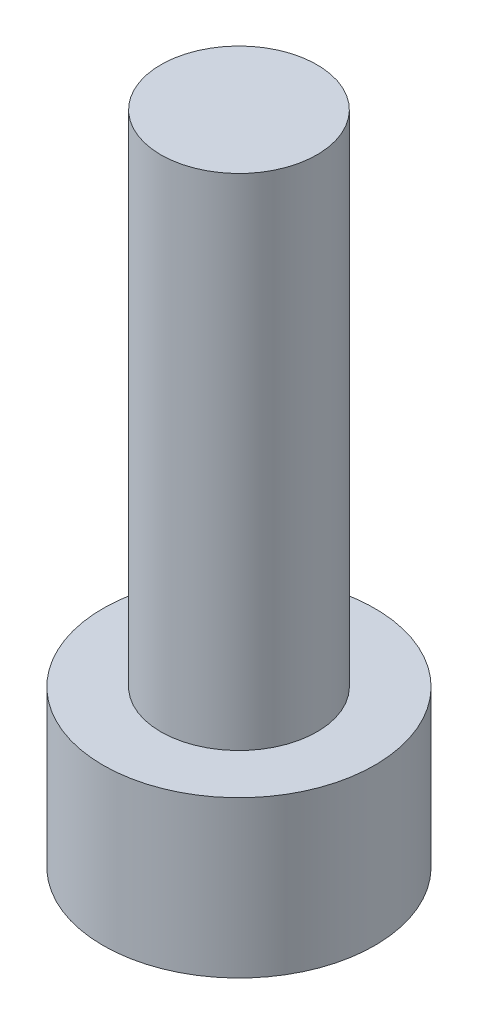
SolidWorks part; units mm, degrees
ref_plane "前视基准面" through (0, 0, 0) normal (0, 0, 1) x (1, 0, 0)
ref_plane "上视基准面" through (0, 0, 0) normal (0, 1, 0) x (1, 0, 0)
ref_plane "右视基准面" through (0, 0, 0) normal (1, 0, 0) x (0, 0, -1)
other "Configuration Table"
sketch "草图1" plane through (0, 0, 0) normal (0, 1, 0) x (1, 0, 0)
  circle A0 centre (0, 0) radius 4.35
  dimension "D1" = 8.7
extrude "凸台-拉伸1" add sketch "草图1" along normal blind 5
sketch "草图2" plane through (0, 5, 0) normal (0, 1, 0) x (1, 0, 0)
  circle A0 centre (0, 0) radius 2.5
  dimension "D1" = 5
extrude "凸台-拉伸2" add sketch "草图2" along normal blind 16
cosmetic thread "装饰螺纹线1"
sketch "草图3" plane through (0, 0, 0) normal (0, -1, 0) x (1, 0, 0)
  line L1 (1.5464, -1.7153) -> (2.2586, 0.4816)
  line L2 (2.2586, 0.4816) -> (0.7123, 2.1968)
  line L3 (0.7123, 2.1968) -> (-1.5464, 1.7153)
  line L4 (-1.5464, 1.7153) -> (-2.2586, -0.4816)
  line L5 (-2.2586, -0.4816) -> (-0.7123, -2.1968)
  line L6 (-0.7123, -2.1968) -> (1.5464, -1.7153)
  circle A0 centre (0, 0) radius 2 construction
  dimension "D1" = 4
extrude "切除-拉伸1" cut sketch "草图3" against normal blind 2.5
